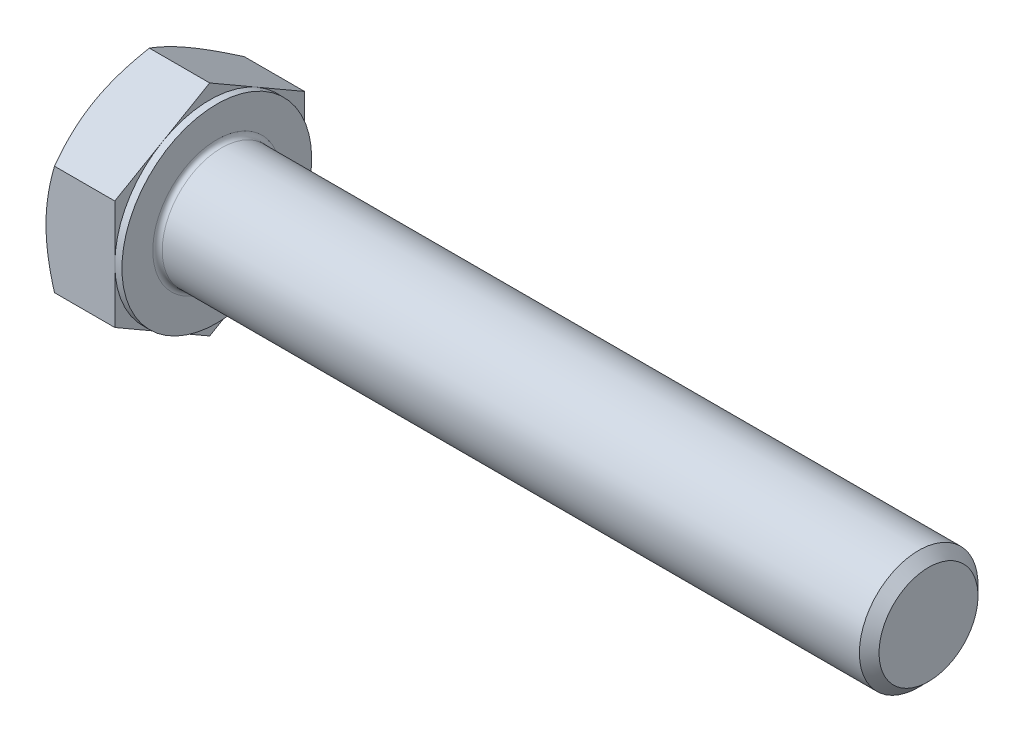
SolidWorks part; units mm, degrees
extrude "BaseHead" add sketch "Sketch1" along normal blind 6.4
sketch "Sketch1" plane through (0, 0, 0) normal (1, 0, 0) x (0, 0, -1)
  line L0 (8, 4.6188) -> (8, -4.6188)
  line L1 (-8, 4.6188) -> (-8, -4.6188)
  line L2 (8, -4.6188) -> (0, -9.2376)
  line L3 (0, -9.2376) -> (-8, -4.6188)
  line L4 (8, 4.6188) -> (0, 9.2376)
  line L5 (0, 9.2376) -> (-8, 4.6188)
  dimension "Width_flats" = 16
  dimension "D2" = 120
  dimension "D3" = 8
  dimension "D4" = 8
  dimension "D5" = 8
revolve "HeadChamfer" cut sketch "Sketch3" angle 360 about L6
sketch "Sketch3" plane through (0, 0, 0) normal (0, 0, 1) x (1, 0, 0)
  line L0 (0, 8) -> (3.6013, 14.2376)
  line L1 (0, 9.2376) -> (0, 4.6188) construction
  line L2 (3.6013, 14.2376) -> (3.6013, 19.2376)
  line L3 (3.6013, 19.2376) -> (-10, 19.2376)
  line L4 (-10, 19.2376) -> (-10, 8)
  line L5 (-10, 8) -> (0, 8)
  line L6 (0, 0) -> (99.06, 0) construction
  line L7 (6.4, 9.2376) -> (0, 9.2376) construction
  dimension "D1" = 8
  dimension "D2" = 5
  dimension "D3" = 10
  dimension "D4" = 5
  dimension "Head_ch_ang" = 30
ref_plane "Plane1" through (0, 0, 0) normal (0, 0, 1) x (1, 0, 0)
ref_plane "Plane2" through (0, 0, 0) normal (0, 1, 0) x (1, 0, 0)
ref_plane "Plane3" through (0, 0, 0) normal (1, 0, 0) x (0, 0, -1)
sketch "BodySke" plane through (0, 0, 0) normal (0, 0, 1) x (1, 0, 0)
  line L0 (0, 4.6188) -> (0, -4.6188) construction
  line L1 (0, 0) -> (66.4, 0)
  line L2 (0, 0) -> (0, 5)
  line L3 (0, 5) -> (65.572, 5)
  line L4 (66.4, 0) -> (66.4, 4.172)
  line L5 (6.4, 9.2376) -> (6.4, 4.6188) construction
  line L6 (66.4, 4.172) -> (65.572, 5)
  line L7 (0, 0) -> (96.52, 0) construction
  line L8 (66.4, -4.172) -> (65.572, -5) construction
  line L9 (0, -5) -> (65.572, -5) construction
  line L10 (7.9, 15.24) -> (7.9, -1.27) construction
  line L12 (6.4, 4.6188) -> (6.4, -4.6188) construction
  dimension "Diameter" = 10
revolve "BaseBody" add sketch "BodySke"
cosmetic thread "ThreadCosmetic" [suppressed]
fillet "HeadFillet" radius 0.4
sketch "Sketch4" plane through (0, 0, 0) normal (0, 0, 1) x (1, 0, 0)
  line L1 (6.4, 9.2376) -> (6.4, 4.6188) construction
  line L2 (6.4, 8) -> (5.8, 8)
  line L3 (6.4, 8) -> (6.4, 19.2376)
  line L4 (6.4, 19.2376) -> (5.8, 19.2376)
  line L5 (0, 0) -> (95.25, 0) construction
  line L6 (0, 0) -> (96.52, 0) construction
  line L7 (5.8, 8) -> (5.8, 19.2376)
  line L8 (6.4, 9.2376) -> (0.7145, 9.2376) construction
  dimension "D2" = 10
  dimension "D1" = 16
revolve "BearingFace" cut sketch "Sketch4" angle 360 about L5
sketch "ThdSchSke" plane through (0, 0, 0) normal (0, 0, 1) x (1, 0, 0)
  line L0 (7.9, -4.172) -> (7.3202, -5)
  line L1 (7.9, -4.172) -> (8.4798, -5)
  line L2 (8.4798, -5) -> (8.4798, -6.25)
  line L3 (-3.175, 0) -> (5.1513, 0) construction
  line L5 (8.4798, -6.25) -> (7.3202, -6.25)
  line L6 (7.3202, -6.25) -> (7.3202, -5)
  dimension "Thread_minor" = 8.344
  dimension "Diameter" = 10
  dimension "Start" = 7.9
revolve "ThreadSchematic" [suppressed] cut sketch "ThdSchSke" angle 360 about L3
pattern_linear "ThdSchPat" [suppressed]
equation "\"D3@Sketch1\" = \"Width_flats@Sketch1\" / 2"
equation "\"D4@Sketch1\" = \"D3@Sketch1\""
equation "\"D5@Sketch1\" = \"D4@Sketch1\""
equation "\"Thread_minor@ThreadCosmetic\" = \"Minor_dia@BodySke\""
equation "\"D1@Sketch3\" = \"Width_flats@Sketch1\" / 2"
equation "\"D1@Sketch4\" = \"Width_flats@Sketch1\""
equation "\"Thread_length@ThreadCosmetic\" = \"Length@BodySke\" - \"Advance@BodySke\""
equation "\"Thread_minor@ThdSchSke\" = \"Minor_dia@BodySke\""
equation "\"Diameter@ThdSchSke\" = \"Diameter@BodySke\""
equation "\"Overcut@ThdSchSke\" = \"Diameter@BodySke\" * 1.25"
equation "\"Start@ThdSchSke\" = \"Head_ht@BaseHead\" + \"Length@BodySke\" - \"Thread_length@ThreadCosmetic\"  '---Non-countersunk---"
equation "\"Num_threads@ThdSchPat\" = int( \"Thread_length@ThreadCosmetic\" / \"Advance@BodySke\" + 0.999 )  + 1"
equation "\"Advance@ThdSchPat\" = \"Thread_length@ThreadCosmetic\" /  (\"Num_threads@ThdSchPat\" - 1) 'relax it"
equation "\"Num_threads@ThdSchPat\" = \"Num_threads@ThdSchPat\" - sgn( \"Num_threads@ThdSchPat\" - 1) '---chamfered tips only---"
